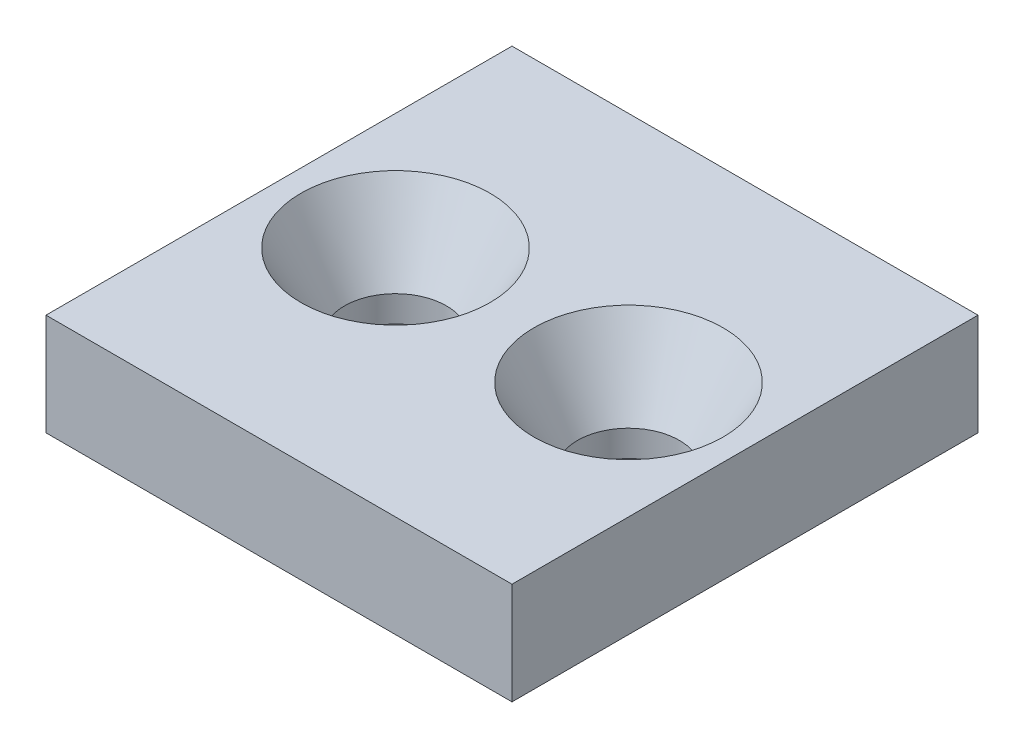
SolidWorks part; units mm, degrees
ref_plane "Front Plane" through (0, 0, 0) normal (0, 0, 1) x (1, 0, 0)
ref_plane "Top Plane" through (0, 0, 0) normal (0, 1, 0) x (1, 0, 0)
ref_plane "Right Plane" through (0, 0, 0) normal (1, 0, 0) x (0, 0, -1)
sketch "Sketch2" plane through (0, 0, 0) normal (0, 1, 0) x (1, 0, 0)
  line L1 (-16, -16) -> (16, -16)
  line L2 (-16, -16) -> (-16, 16)
  line L3 (-16, 16) -> (16, 16)
  line L4 (16, -16) -> (16, 16)
  line L5 (-16, -16) -> (16, 16) construction
  line L6 (-16, 16) -> (16, -16) construction
  point P0 (0, 0)
  dimension "D1" = 32
  dimension "D2" = 32
extrude "Boss-Extrude1" add sketch "Sketch2" along normal blind 7
sketch "Sketch5" plane through (0, 7, 0) normal (0, 1, 0) x (1, 0, 0)
  line L0 (0, 16) -> (0, -16) construction
  line L1 (16, 16) -> (-16, 16) construction
  line L2 (-16, -16) -> (16, -16) construction
  line L3 (16, 0) -> (-16, 0) construction
  line L4 (16, -16) -> (16, 16) construction
  line L5 (-16, 16) -> (-16, -16) construction
  point P12 (-8, 0)
  point P13 (8, 0)
  dimension "D1" = 8
  dimension "D2" = 8
hole_wizard "CSK for M6 Flat Head Machine Screw1" positions "3DSketch2" profile "Sketch6" countersink size "M6" standard "ANSI Metric" end condition through all
sketch3d "3DSketch2"
  point P0 (-8, 7, 0)
  point P3 (8, 7, 0)
sketch "Sketch6" plane through (-8, 7, 0) normal (1, 0, 0) x (0, 0, 1)
  line L0 (0, 0) -> (0, 7)
  line L1 (0, 7) -> (3.5, 7)
  line L2 (3.5, 7) -> (3.5, 5.1962)
  line L3 (3.5, 5.1962) -> (6.5, 0)
  line L5 (6.5, 0) -> (0, 0)
  line L6 (-3.5, 5.1962) -> (-6.5, 0) construction
  line L11 (0, -6.35) -> (0, 107.95) construction
  dimension "Thru Hole Dia." = 7
  dimension "Thru Hole Depth" = 7
  dimension "Near C'Sink Dia." = 13
  dimension "Near C'Sink Angle" = 60
